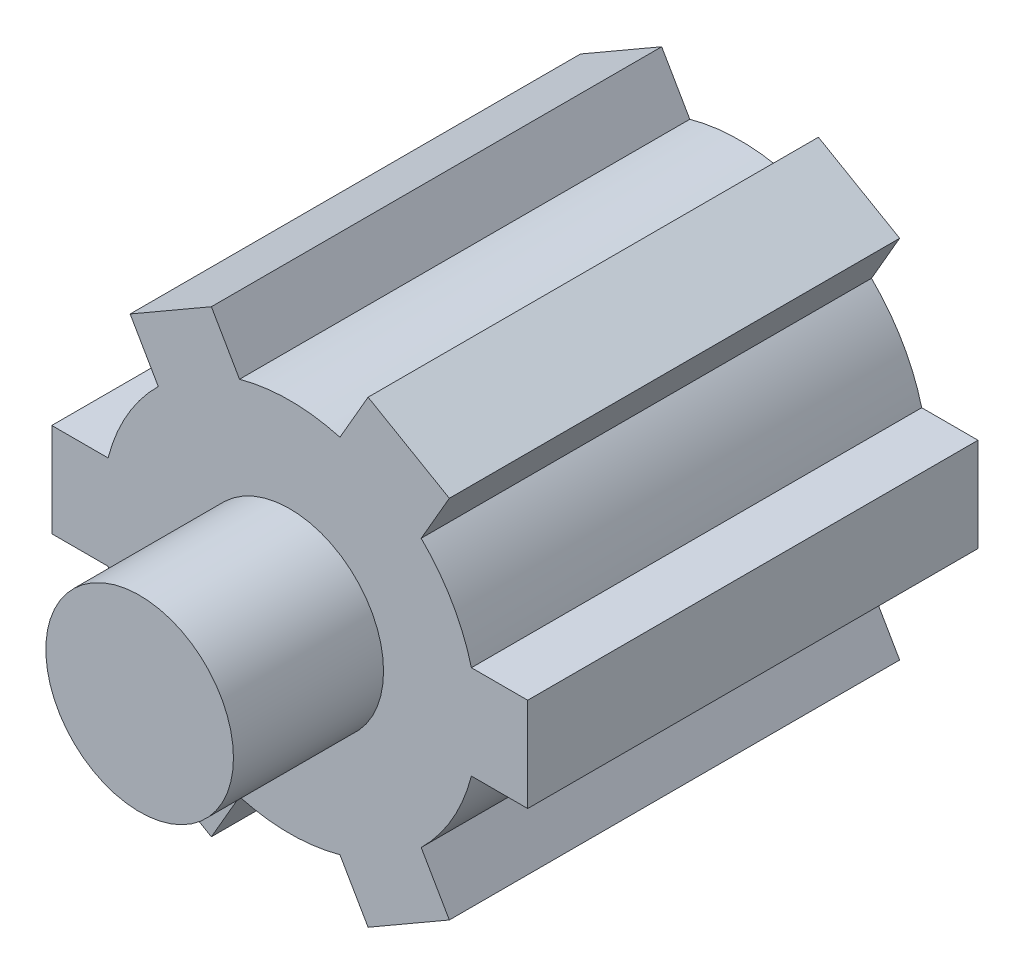
SolidWorks part; units mm, degrees
ref_plane "Front Plane" through (0, 0, 0) normal (0, 0, 1) x (1, 0, 0)
ref_plane "Top Plane" through (0, 0, 0) normal (0, 1, 0) x (1, 0, 0)
ref_plane "Right Plane" through (0, 0, 0) normal (1, 0, 0) x (0, 0, -1)
sketch "Sketch1" plane through (0, 0, 0) normal (0, 0, 1) x (1, 0, 0)
  line L0 (0, 0) -> (-17.2396, 0) construction
  line L1 (-10.0667, 1.9844) -> (-10.0667, -1.9844)
  line L2 (-10.0667, 1.9844) -> (-7.6855, 1.9844)
  line L3 (-10.0667, -1.9844) -> (-7.6855, -1.9844)
  line L4 (-3.3148, 9.7102) -> (-2.1242, 7.648)
  line L5 (-3.3148, 9.7102) -> (-6.7519, 7.7258)
  line L6 (-6.7519, 7.7258) -> (-5.5612, 5.6636)
  line L7 (6.7519, 7.7258) -> (5.5612, 5.6636)
  line L8 (6.7519, 7.7258) -> (3.3148, 9.7102)
  line L9 (3.3148, 9.7102) -> (2.1242, 7.648)
  line L10 (10.0667, -1.9844) -> (7.6855, -1.9844)
  line L11 (10.0667, -1.9844) -> (10.0667, 1.9844)
  line L12 (10.0667, 1.9844) -> (7.6855, 1.9844)
  line L13 (3.3148, -9.7102) -> (2.1242, -7.648)
  line L14 (3.3148, -9.7102) -> (6.7519, -7.7258)
  line L15 (6.7519, -7.7258) -> (5.5612, -5.6636)
  line L16 (-6.7519, -7.7258) -> (-5.5612, -5.6636)
  line L17 (-6.7519, -7.7258) -> (-3.3148, -9.7102)
  line L18 (-3.3148, -9.7102) -> (-2.1242, -7.648)
  arc A0 (-7.6855, -1.9844) -> (-5.5612, -5.6636) centre (0, 0) ccw
  arc A1 (-5.5612, 5.6636) -> (-7.6855, 1.9844) centre (0, 0) ccw
  arc A2 (2.1242, 7.648) -> (-2.1242, 7.648) centre (0, 0) ccw
  arc A3 (7.6855, 1.9844) -> (5.5612, 5.6636) centre (0, 0) ccw
  arc A4 (5.5612, -5.6636) -> (7.6855, -1.9844) centre (0, 0) ccw
  arc A5 (-2.1242, -7.648) -> (2.1242, -7.648) centre (0, 0) ccw
  point P4 (-10.0667, 0)
  point P27 (4.1281, 0.8943)
  dimension "D1" = 15.875
  dimension "D2" = 3.9688
  dimension "D3" = 2.3813
extrude "Boss-Extrude1" add sketch "Sketch1" along normal mid plane 19.05
sketch "Sketch2" plane through (0, 0, 9.525) normal (0, 0, 1) x (1, 0, 0)
  circle A0 centre (0, 0) radius 3.9688
  dimension "D1" = 7.9375
extrude "Boss-Extrude2" add sketch "Sketch2" along normal blind 6.35
